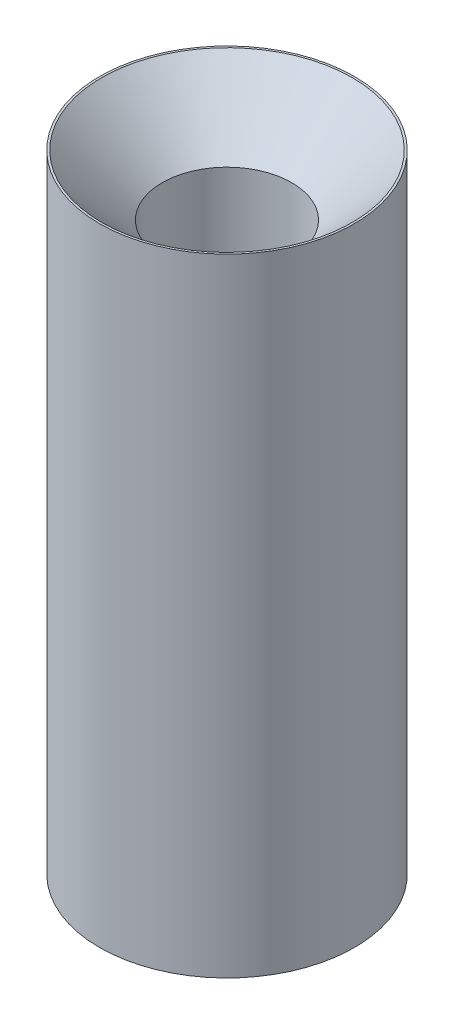
SolidWorks part; units mm, degrees
ref_plane "Front Plane" through (0, 0, 0) normal (0, 0, 1) x (1, 0, 0)
ref_plane "Top Plane" through (0, 0, 0) normal (0, 1, 0) x (1, 0, 0)
ref_plane "Right Plane" through (0, 0, 0) normal (1, 0, 0) x (0, 0, -1)
sketch "Sketch1" plane through (0, 0, 0) normal (0, 1, 0) x (1, 0, 0)
  circle A0 centre (0, 0) radius 3.05
  dimension "D1" = 6.1
extrude "Boss-Extrude1" add sketch "Sketch1" along normal blind 15
hole_wizard "CSK for M3 Flat Head Machine Screw1" positions "Sketch2" profile "Sketch3" countersink size "M3" standard "ANSI Metric"
sketch "Sketch2" plane through (0, 15, 0) normal (0, 1, 0) x (1, 0, 0)
  point P0 (0, 0)
sketch "Sketch3" plane through (0, 15, 0) normal (1, 0, 0) x (0, 0, 1)
  line L0 (0, 0) -> (0, 55)
  line L1 (0, 55) -> (1.55, 54.0687)
  line L2 (1.55, 54.0687) -> (1.55, 1.45)
  line L3 (1.55, 1.45) -> (3, 0)
  line L5 (3, 0) -> (0, 0)
  line L6 (-1.55, 1.45) -> (-3, 0) construction
  line L10 (0, 55) -> (-1.55, 54.0687) construction
  line L11 (0, -6.35) -> (0, 107.95) construction
  dimension "Hole Dia." = 3.1
  dimension "Hole Depth" = 55
  dimension "Near C'Sink Dia." = 6
  dimension "Near C'Sink Angle" = 90
  dimension "Drill Angle" = 118
